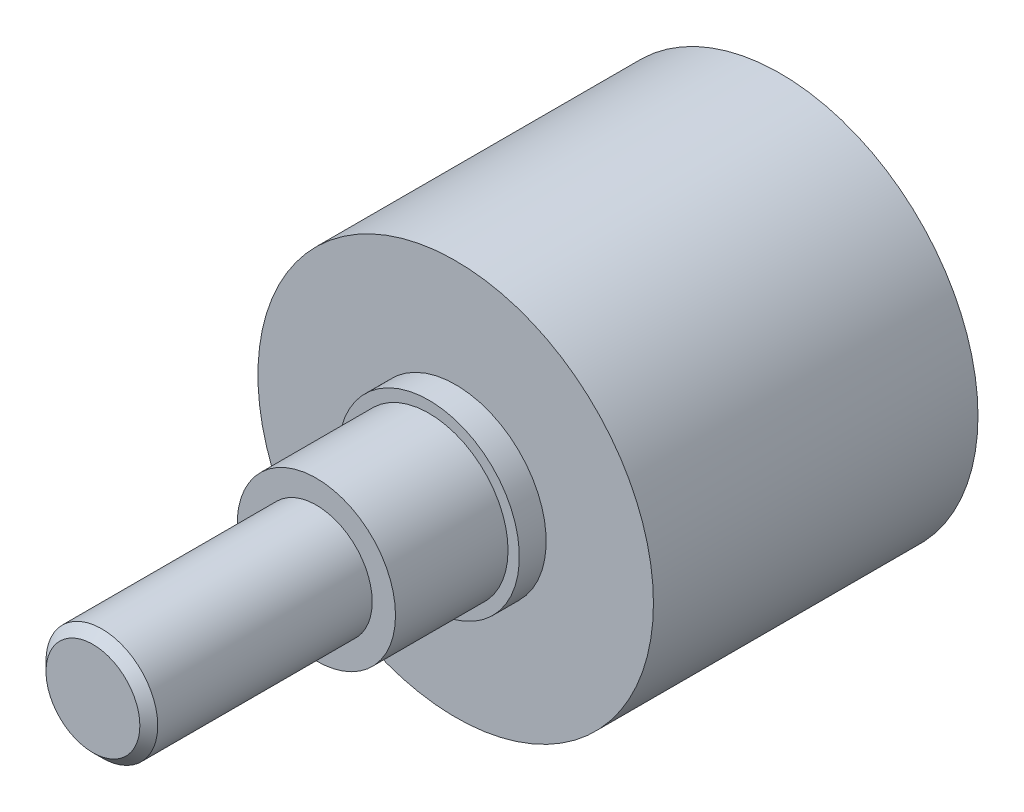
SolidWorks part; units mm, degrees
material "6061-T6 (SS)"
ref_plane "Front Plane" through (0, 0, 0) normal (0, 0, 1) x (1, 0, 0)
ref_plane "Top Plane" through (0, 0, 0) normal (0, 1, 0) x (1, 0, 0)
ref_plane "Right Plane" through (0, 0, 0) normal (1, 0, 0) x (0, 0, -1)
sketch "Sketch1" plane through (0, 0, 0) normal (0, 0, 1) x (1, 0, 0)
  circle A0 centre (0, 0) radius 11.2395
  dimension "D1" = 22.479
extrude "Body" add sketch "Sketch1" along normal blind 18.446
sketch "Sketch2" plane through (0, 0, 18.446) normal (0, 0, 1) x (1, 0, 0)
  circle A0 centre (0, 0) radius 5.1435
  dimension "D1" = 10.287
extrude "Lip" add sketch "Sketch2" along normal blind 1.524
sketch "Sketch3" plane through (0, 0, 19.97) normal (0, 0, 1) x (1, 0, 0)
  circle A0 centre (0, 0) radius 4.5
  dimension "D1" = 9
extrude "Threading" add sketch "Sketch3" along normal blind 6.396
sketch "Sketch4" plane through (0, 0, 18.446) normal (0, 0, 1) x (1, 0, 0)
  circle A0 centre (0, 0) radius 3.175
  dimension "D1" = 6.35
extrude "Shaft" add sketch "Sketch4" along normal blind 20.617
chamfer "Chamfer1" distance 0.508 angle 45 1 edges at (3.175, 0, 39.063)
